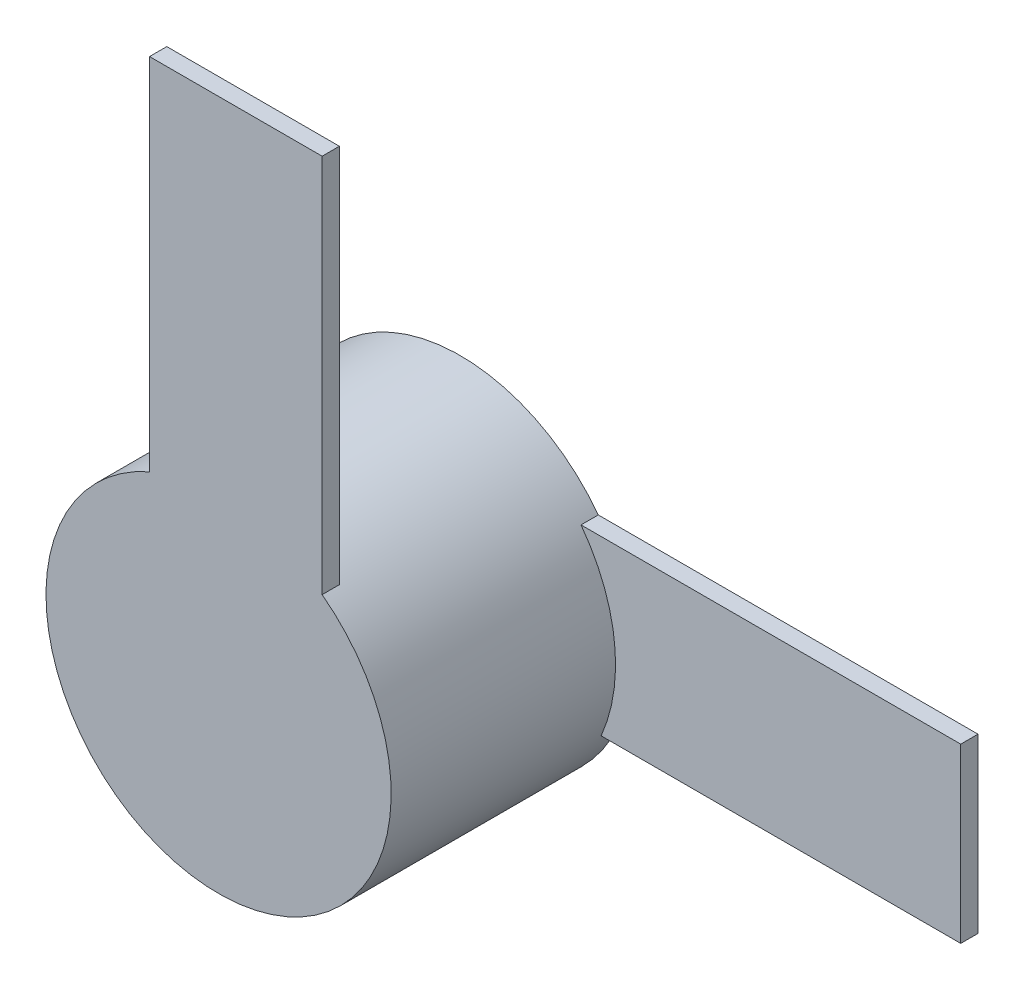
SolidWorks part; units mm, degrees
ref_plane "Front Plane" through (0, 0, 0) normal (0, 0, 1) x (1, 0, 0)
ref_plane "Top Plane" through (0, 0, 0) normal (0, 1, 0) x (1, 0, 0)
ref_plane "Right Plane" through (0, 0, 0) normal (1, 0, 0) x (0, 0, -1)
sketch "Sketch1" plane through (0, 0, 0) normal (0, 0, 1) x (1, 0, 0)
  circle A0 centre (0, 0) radius 50
  dimension "D1" = 100
extrude "Boss-Extrude1" add sketch "Sketch1" along normal blind 70
sketch "Sketch2" plane through (0, 0, 0) normal (0, 1, 0) x (1, 0, 0)
  line L0 (-50, -70) -> (50, -70) construction
  line L1 (-20, -70) -> (30, -70)
  line L2 (-20, -70) -> (-20, -65)
  line L3 (-20, -65) -> (30, -65)
  line L4 (30, -70) -> (30, -65)
  line L5 (50, -70) -> (50, 0) construction
  dimension "D1" = 50
  dimension "D2" = 5
  dimension "D3" = 20
extrude "Boss-Extrude2" add sketch "Sketch2" along normal blind 150
sketch "Sketch4" plane through (0, 0, 0) normal (1, 0, 0) x (0, 0, -1)
  line L0 (0, -50) -> (0, 50) construction
  line L1 (0, 30) -> (-5, 30)
  line L2 (0, 30) -> (0, -20)
  line L3 (0, -20) -> (-5, -20)
  line L4 (-5, 30) -> (-5, -20)
  line L5 (0, 50) -> (-65, 50) construction
  point P6 (-2.5, 30)
  dimension "D1" = 50
  dimension "D2" = 5
  dimension "D3" = 20
extrude "Boss-Extrude3" add sketch "Sketch4" along normal blind 150
